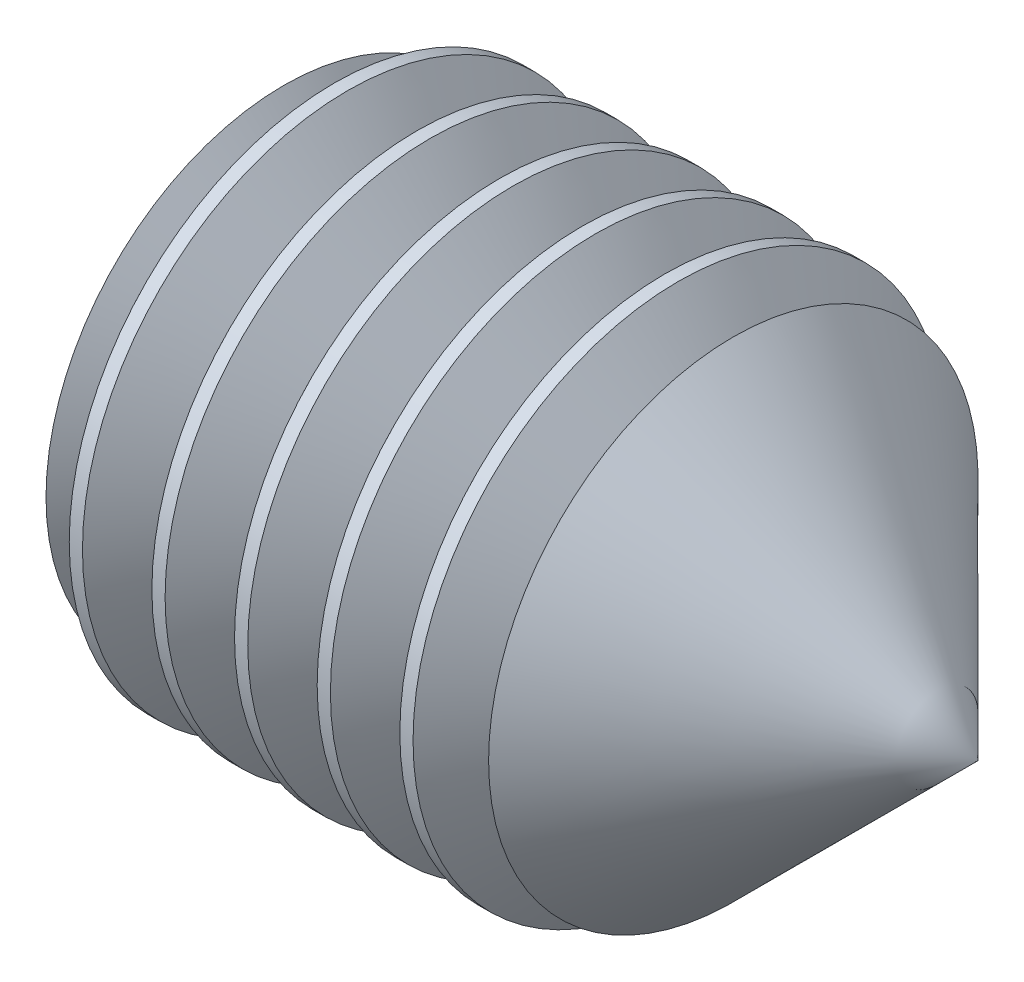
SolidWorks part; units mm, degrees
revolve "BaseBody" add sketch "BodySke" angle 360 about L5
sketch "BodySke" plane through (0, 0, 0) normal (0, 0, 1) x (1, 0, 0)
  line L0 (0, 0) -> (0, 1.2195)
  line L1 (0, 1.2195) -> (0.1619, 1.5)
  line L2 (0.1619, 1.5) -> (2.5, 1.5)
  line L3 (2.5, 1.5) -> (4, 0)
  line L4 (4, 0) -> (0, 0)
  line L5 (-12.7, 0) -> (88.9, 0) construction
  line L6 (2.5, -1.5) -> (4, 0) construction
  line L7 (0.25, 15.875) -> (0.25, -3.175) construction
  line L8 (0, -1.2195) -> (0.1619, -1.5) construction
  dimension "Diameter" = 3
  dimension "Drive_ch_ang" = 60
  dimension "Minor_dia" = 2.439
  dimension "Advance" = 0.5
  dimension "Cone_ang" = 90
  dimension "Length" = 4
cosmetic thread "ThreadCosmetic" [suppressed] parameters "Thread_minor"=2.439
material "AISI 1045 Aço, trefilado"
ref_plane "Plane1" through (0, 0, 0) normal (0, 0, 1) x (1, 0, 0)
ref_plane "Plane2" through (0, 0, 0) normal (0, 1, 0) x (1, 0, 0)
ref_plane "Plane3" through (0, 0, 0) normal (1, 0, 0) x (0, 0, -1)
sketch "Sketch2" plane through (0, 0, 0) normal (-1, 0, 0) x (0, 0, 1)
  line L0 (0.433, 0.75) -> (-0.433, 0.75)
  line L1 (-0.433, 0.75) -> (-0.866, 0)
  line L2 (0.433, 0.75) -> (0.866, 0)
  line L3 (0.433, -0.75) -> (0.866, 0)
  line L4 (0.433, -0.75) -> (-0.433, -0.75)
  line L5 (-0.433, -0.75) -> (-0.866, 0)
  dimension "Hex_size" = 1.5
  dimension "D2" = 0.75
  dimension "D3" = 0.75
extrude "Hex" cut sketch "Sketch2" against normal blind 2
sketch "ThdSchSke" plane through (0, 0, 0) normal (0, 0, 1) x (1, 0, 0)
  line L0 (0.1619, -1.2195) -> (-0.0345, -1.5)
  line L1 (0.1619, -1.2195) -> (0.3584, -1.5)
  line L2 (0.3584, -1.5) -> (0.3584, -1.875)
  line L3 (-3.175, 0) -> (5.1513, 0) construction
  line L4 (0.1619, 1.5) -> (0.1619, -1.5) construction
  line L5 (0.3584, -1.875) -> (-0.0345, -1.875)
  line L6 (-0.0345, -1.875) -> (-0.0345, -1.5)
  dimension "Thread_minor" = 2.439
  dimension "Diameter" = 3
revolve "ThreadSchematic" cut sketch "ThdSchSke" angle 360 about L3
pattern_linear "ThdSchPat" count 6 spacing 0.4676 along (1, 0, 0) of "ThreadSchematic"
equation "\"D2@Sketch2\" = \"Hex_size@Sketch2\" / 2"
equation "\"D3@Sketch2\" = \"Hex_size@Sketch2\" / 2"
equation "\"Thread_minor@ThreadCosmetic\" = \"Minor_dia@BodySke\""
equation "\"Thread_minor@ThdSchSke\" = \"Thread_minor@ThreadCosmetic\""
equation "\"Diameter@ThdSchSke\" = \"Diameter@BodySke\""
equation "\"Overcut@ThdSchSke\" = \"Diameter@BodySke\" * 1.25"
equation "\"Num_threads@ThdSchPat\" = int( (\"Length@BodySke\" - ( ( ( \"Diameter@BodySke\" - \"Minor_dia@BodySke\" ) * 0.5 ) / tan( \"Drive_ch_ang@BodySke\" * 0.017453292 ) ) - ( ( \"Diameter@BodySke\" * 0.5 ) / tan( \"Cone_ang@BodySke\" * 0.008726646 ) ) ) / \"Advance@BodySke\" + 0.999 )  + 1"
equation "\"Advance@ThdSchPat\" = (\"Length@BodySke\" - ( ( ( \"Diameter@BodySke\" - \"Minor_dia@BodySke\" ) * 0.5 ) / tan( \"Drive_ch_ang@BodySke\" * 0.017453292 ) ) - ( ( \"Diameter@BodySke\" * 0.5 ) / tan( \"Cone_ang@BodySke\" * 0.008726646 ) ) ) /  (\"Num_threads@ThdSchPat\" - 1) 'relax it"
equation "' \"Num_threads@ThdSchPat\" = \"Num_threads@ThdSchPat\" - sgn( \"Num_threads@ThdSchPat\" - 1) '---chamfered tips only---"
